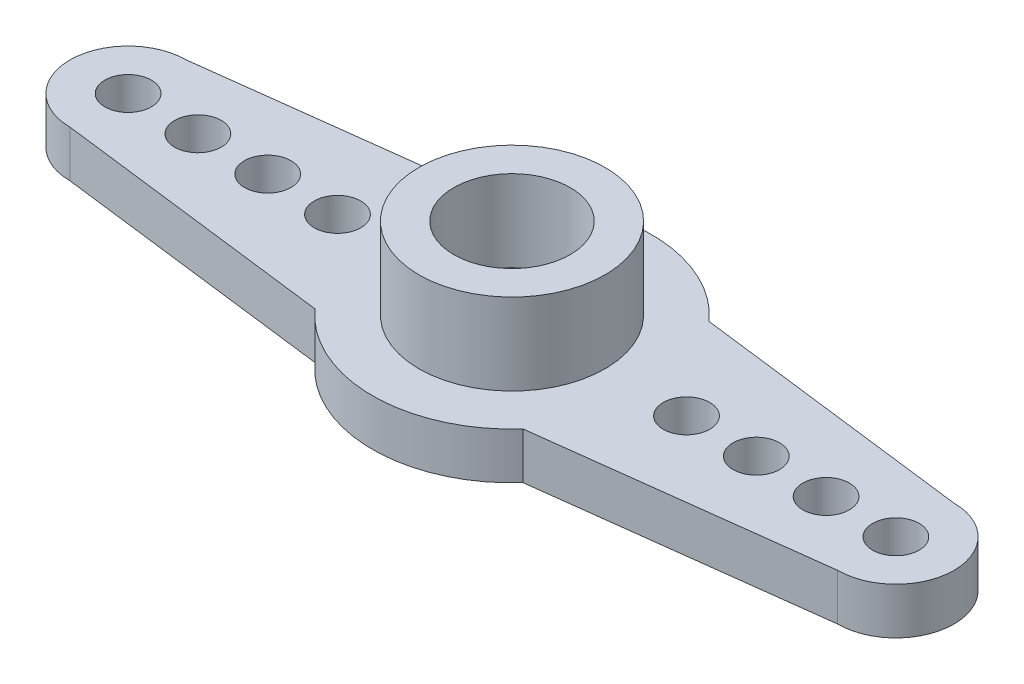
SolidWorks part; units mm, degrees
ref_plane "Front Plane" through (0, 0, 0) normal (0, 0, 1) x (1, 0, 0)
ref_plane "Top Plane" through (0, 0, 0) normal (0, 1, 0) x (1, 0, 0)
ref_plane "Right Plane" through (0, 0, 0) normal (1, 0, 0) x (0, 0, -1)
sketch "Sketch1" plane through (0, 0, 0) normal (0, 1, 0) x (1, 0, 0)
  line L0 (-19, 0) -> (19, 0) construction
  line L1 (-16.5, 2.5) -> (-4.4721, 4)
  line L2 (-16.5, -2.5) -> (-4.4721, -4)
  line L3 (-4.4721, 4) -> (-4.4721, -4) construction
  line L4 (16.5, 2.5) -> (4.4721, 4)
  line L5 (16.5, -2.5) -> (4.4721, -4)
  line L6 (4.4721, -4) -> (4.4721, 4) construction
  arc A0 (-4.4721, -4) -> (4.4721, -4) centre (0, 0) ccw
  arc A1 (16.5, -2.5) -> (16.5, 2.5) centre (16.5, 0) ccw
  arc A2 (-16.5, 2.5) -> (-16.5, -2.5) centre (-16.5, 0) ccw
  arc A3 (4.4721, 4) -> (-4.4721, 4) centre (0, 0) ccw
  point P14 (0, 0)
  dimension "D1" = 12
  dimension "D2" = 5
  dimension "D3" = 38
  dimension "D4" = 8
extrude "Boss-Extrude1" add sketch "Sketch1" along normal blind 2
sketch "Sketch2" plane through (0, 2, 0) normal (0, 1, 0) x (1, 0, 0)
  circle A0 centre (0, 0) radius 2.5
  circle A1 centre (0, 0) radius 4
  dimension "D1" = 5
  dimension "D2" = 1.5
extrude "Boss-Extrude2" add sketch "Sketch2" along normal blind 3.5
sketch "Sketch3" plane through (0, 2, 0) normal (0, 1, 0) x (1, 0, 0)
  circle A0 centre (0, 0) radius 1.5
  dimension "D1" = 3
extrude "Cut-Extrude1" cut sketch "Sketch3" against normal blind 5
sketch "Sketch4" plane through (0, 0, 0) normal (0, -1, 0) x (1, 0, 0)
  circle A0 centre (0, 0) radius 3
  dimension "D1" = 6
extrude "Cut-Extrude2" cut sketch "Sketch4" against normal blind 1
sketch "Sketch5" plane through (0, 0, 0) normal (0, -1, 0) x (1, 0, 0)
  line L0 (0, 0) -> (0, 6) construction
  circle A0 centre (16.5, 0) radius 1
  circle A1 centre (13.5, 0) radius 1
  circle A2 centre (10.5, 0) radius 1
  circle A3 centre (7.5, 0) radius 1
  arc A4 (4.4721, 4) -> (-4.4721, 4) centre (0, 0) ccw construction
  circle A5 centre (-16.5, 0) radius 1
  circle A6 centre (-13.5, 0) radius 1
  circle A7 centre (-10.5, 0) radius 1
  circle A8 centre (-7.5, 0) radius 1
  dimension "D1" = 2
  dimension "D2" = 4
extrude "Cut-Extrude3" cut sketch "Sketch5" against normal blind 5 contours A5 | A7 | A8 | A3 | A2 | A1 | A0 | A6
